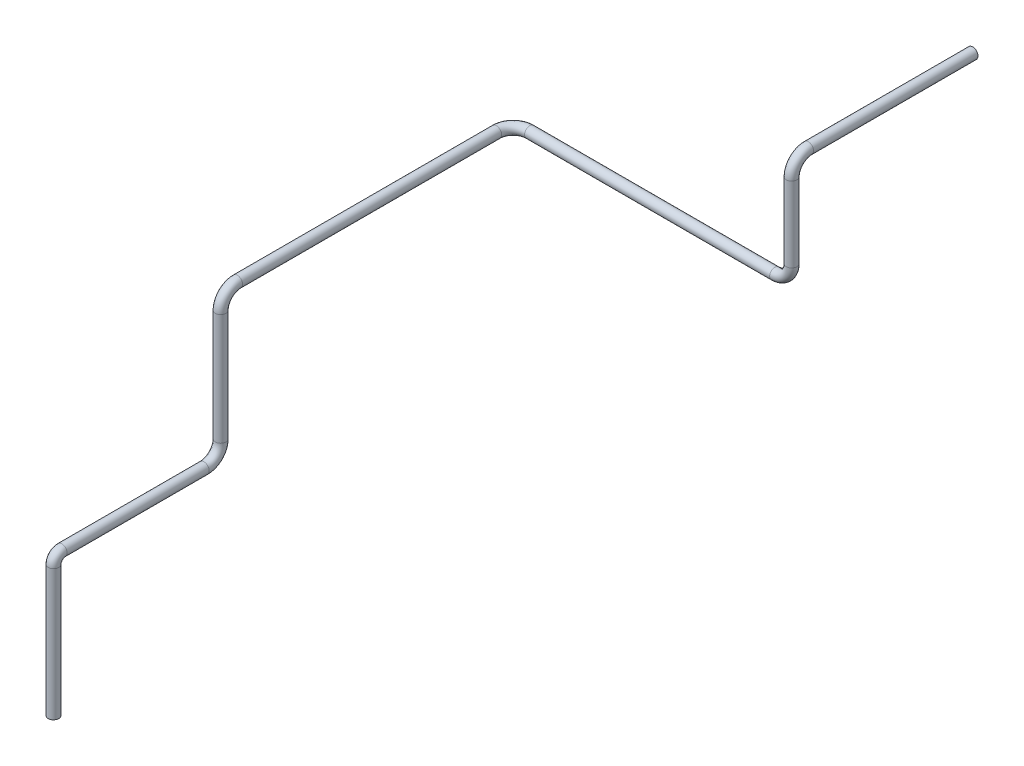
SolidWorks part; units mm, degrees
ref_plane "Alzado" through (0, 0, 0) normal (0, 0, 1) x (1, 0, 0)
ref_plane "Planta" through (0, 0, 0) normal (0, 1, 0) x (1, 0, 0)
ref_plane "Vista lateral" through (0, 0, 0) normal (1, 0, 0) x (0, 0, -1)
sketch "Croquis1" plane through (0, 0, 0) normal (0, 0, 1) x (1, 0, 0)
  circle A0 centre (0, 0) radius 19.05
  dimension "D1" = 38.1
extrude "Saliente-Extruir1" add sketch "Croquis1" along normal blind 100
sketch3d "Croquis3D2"
  line L0 (0, 0, 100) -> (0, 0, 590)
  line L1 (0, 0, 100) -> (0, 0, 0) construction
  line L2 (0, -60, 650) -> (0, -330, 650)
  line L3 (-60, -390, 650) -> (-940, -390, 650)
  line L4 (-1000, -390, 710) -> (-1000, -390, 1640)
  line L5 (-1000, -450, 1700) -> (-1000, -850, 1700)
  line L6 (-1000, -910, 1760) -> (-1000, -910, 2270)
  line L7 (-1000, -940, 2300) -> (-1000, -1410, 2300)
  arc A0 (-1000, -850, 1700) -> (-1000, -910, 1760) centre (-1000, -850, 1760) ccw
  arc A1 (-1000, -390, 1640) -> (-1000, -450, 1700) centre (-1000, -450, 1640) ccw
  arc A2 (-940, -390, 650) -> (-1000, -390, 710) centre (-940, -390, 710) ccw
  arc A3 (0, -330, 650) -> (-60, -390, 650) centre (-60, -330, 650) ccw
  arc A4 (0, 0, 590) -> (0, -60, 650) centre (0, -60, 590) ccw
  arc A5 (-1000, -910, 2270) -> (-1000, -940, 2300) centre (-1000, -940, 2270) ccw
  point P12 (-1000, -910, 1700)
  point P13 (-1060, -850, 1760)
  point P16 (-1000, -390, 1700)
  point P17 (-940, -450, 1640)
  point P20 (-1000, -390, 650)
  point P21 (-940, -330, 710)
  point P24 (0, -390, 650)
  point P25 (-60, -330, 590)
  point P28 (0, 0, 650)
  point P29 (60, -60, 590)
  point P32 (-1000, -910, 2300)
  point P33 (-970, -940, 2270)
  dimension "D8" = 60
  dimension "D9" = 30
  dimension "D1" = 550
  dimension "D2" = 390
  dimension "D3" = 1000
  dimension "D4" = 1050
  dimension "D5" = 520
  dimension "D6" = 600
  dimension "D7" = 500
sketch "Croquis2" plane through (0, 0, 100) normal (0, 0, 1) x (1, 0, 0)
  circle A0 centre (0, 0) radius 19.05
  dimension "D1" = 38.1
sweep "Barrer1" add profiles "Croquis2" path "Croquis3D2"
